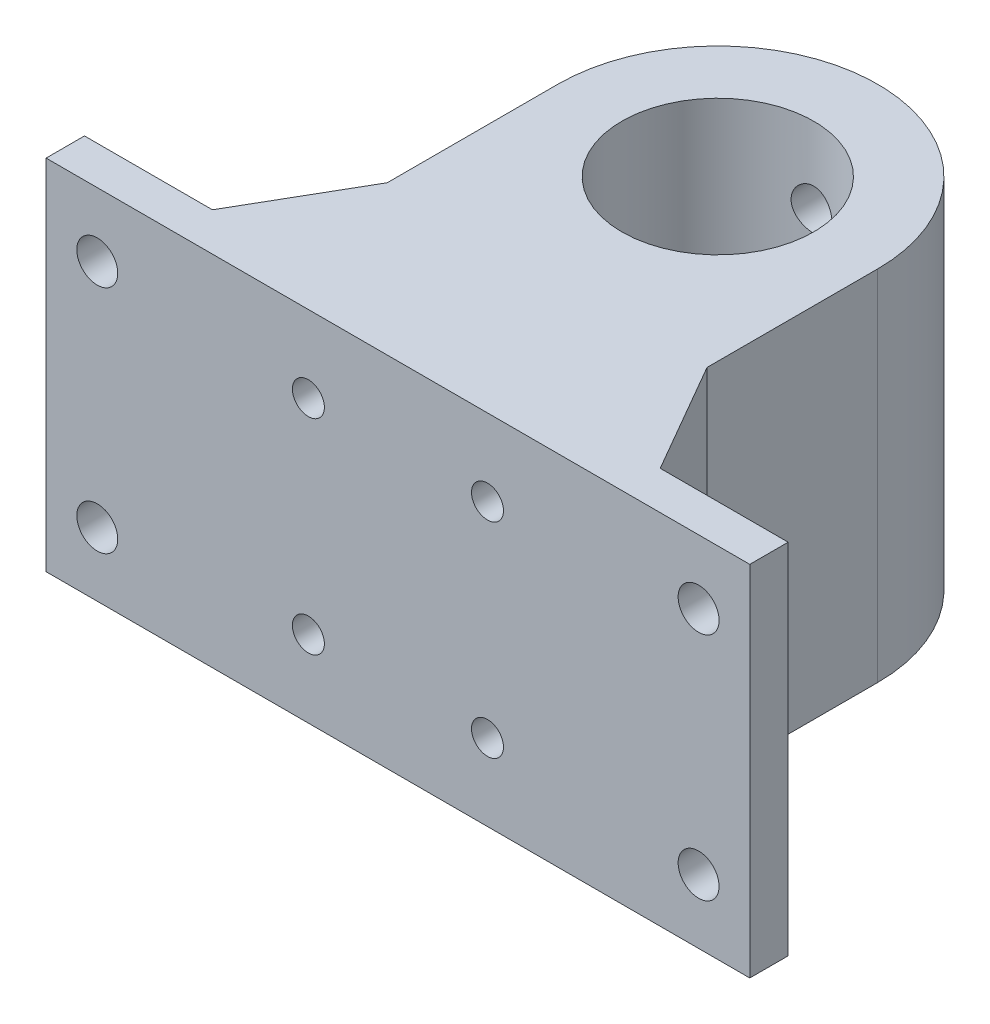
SolidWorks part; units mm, degrees
material "6061 合金"
ref_plane "前视基准面" through (0, 0, 0) normal (0, 0, 1) x (1, 0, 0)
ref_plane "上视基准面" through (0, 0, 0) normal (0, 1, 0) x (1, 0, 0)
ref_plane "右视基准面" through (0, 0, 0) normal (1, 0, 0) x (0, 0, -1)
sketch "草图1" plane through (0, 0, 0) normal (0, 1, 0) x (1, 0, 0)
  line L2 (-12.5, -25) -> (12.5, -25)
  line L3 (-12.5, -25) -> (-12.5, 0)
  line L5 (12.5, -25) -> (12.5, 0)
  arc A0 (12.5, 0) -> (-12.5, 0) centre (0, 0) ccw
  circle A1 centre (0, 0) radius 7.5
  point P3 (0, -12.5)
  dimension "D1" = 25
  dimension "D3" = 15
extrude "凸台-拉伸1" add sketch "草图1" along normal mid plane 28
sketch "草图7" plane through (0, 0, 0) normal (0, 0, 1) x (1, 0, 0)
  line L0 (0, 0) -> (9.3494, 0) construction
  circle A0 centre (0, -8) radius 1.6
  circle A1 centre (0, 8) radius 1.6
  dimension "D1" = 8
extrude "切除-拉伸2" cut sketch "草图7" against normal through all
hole_wizard "M3 螺纹孔1" positions "3D草图1" profile "草图8" tap size "M3" standard "GB"
sketch3d "3D草图1"
  point P0 (-7, -8, 25)
  point P7 (7, -8, 25)
  point P9 (7, 8, 25)
  point P11 (-7, 8, 25)
sketch "草图8" plane through (-7, -8, 25) normal (1, 0, 0) x (0, -1, 0)
  line L0 (0, 0) -> (0, 10.2511)
  line L1 (0, 10.2511) -> (1.25, 9.5)
  line L2 (1.25, 9.5) -> (1.25, 0)
  line L5 (1.25, 0) -> (0, 0)
  line L10 (0, 10.2511) -> (-1.25, 9.5) construction
  line L11 (0, -6.35) -> (0, 107.95) construction
  dimension "螺纹孔钻头直径" = 2.5
  dimension "螺纹孔钻头深度" = 9.5
  dimension "导头角度" = 118
cosmetic thread "孔螺蚊线1" parameters "D1"=8, "D2"=3
cosmetic thread "孔螺蚊线2" parameters "D1"=8, "D2"=3
cosmetic thread "孔螺蚊线3" parameters "D1"=8, "D2"=3
cosmetic thread "孔螺蚊线4" parameters "D1"=8, "D2"=3
sketch "草图9" plane through (12.5, 0, 0) normal (1, 0, 0) x (0, 0, -1)
  line L0 (-25, 14) -> (0, 14) construction
  line L1 (-25, -14) -> (-22, -14)
  line L2 (-25, -14) -> (-25, 14)
  line L3 (-25, 14) -> (-22, 14)
  line L4 (-22, -14) -> (-22, 14)
  dimension "D1" = 3
extrude "凸台-拉伸2" add sketch "草图9" along normal blind 15
sketch "草图10" plane through (0, 0, 22) normal (0, 0, -1) x (-1, 0, 0)
  line L0 (-12.5, 0) -> (-27.5, 0) construction
  line L3 (-12.5, -14) -> (-12.5, 14) construction
  line L4 (-27.5, -14) -> (-27.5, 14) construction
  line L5 (-27.5, 14) -> (-12.5, 14) construction
  circle A0 centre (-23.5, 9) radius 1.6
  circle A1 centre (-23.5, -9) radius 1.6
  dimension "D1" = 4
  dimension "D2" = 3.2
  dimension "D3" = 5
extrude "切除-拉伸3" cut sketch "草图10" against normal through all
ref_plane "基准面1" through (0, 0, 0) normal (1, 0, 0) x (0, 0, -1)
mirror "镜向6" about plane through (0, 0, 0) normal (1, 0, 0) of "切除-拉伸3", "凸台-拉伸2"
chamfer "倒角1" distance 5 angle 60 2 edges at (12.5, 0, 22) (-12.5, 0, 22)
